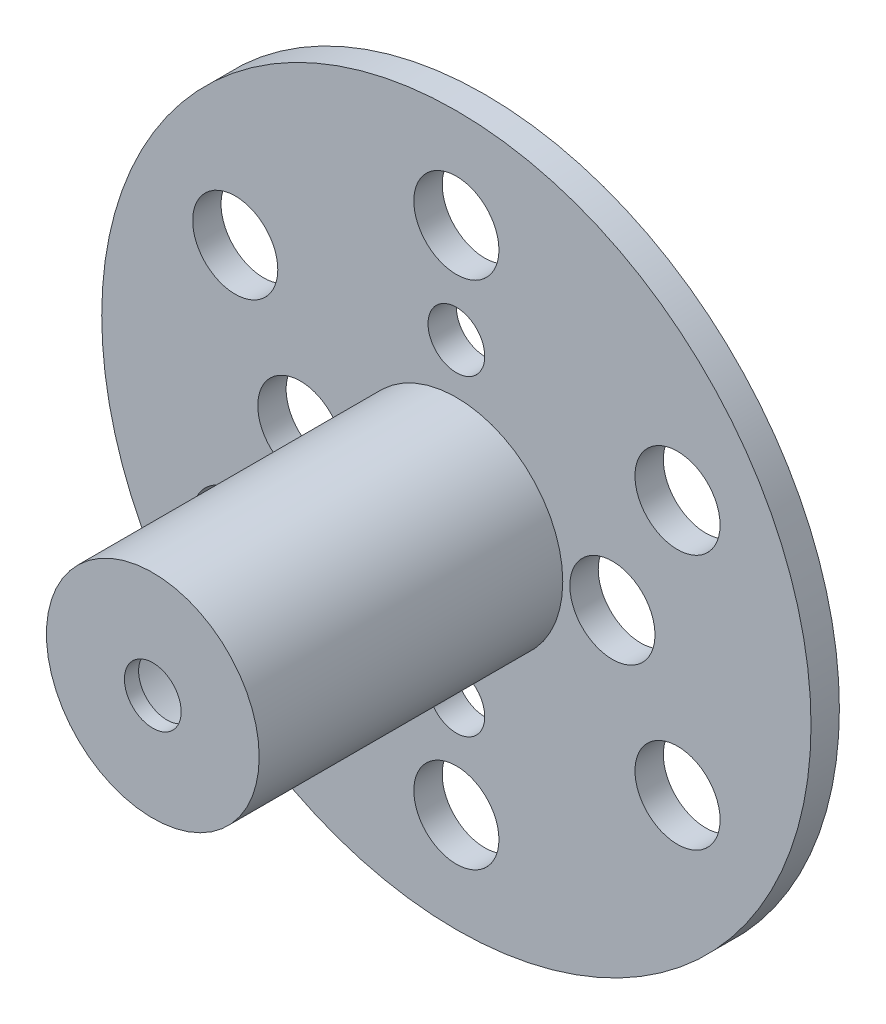
SolidWorks part; units mm, degrees
material "ABS"
ref_plane "Спереди" through (0, 0, 0) normal (0, 0, 1) x (1, 0, 0)
ref_plane "Сверху" through (0, 0, 0) normal (0, 1, 0) x (1, 0, 0)
ref_plane "Справа" through (0, 0, 0) normal (1, 0, 0) x (0, 0, -1)
sketch "Эскиз1" plane through (0, 0, 0) normal (0, 0, 1) x (1, 0, 0)
  line L0 (0, 0) -> (0, 9) construction
  line L1 (0, 0) -> (-50000, 0) construction
  circle A0 centre (0, 0) radius 2.75
  circle A1 centre (0, 0) radius 12.5
  circle A2 centre (0, 9) radius 1.5
  circle A3 centre (7.7942, 4.5) radius 1.5
  circle A4 centre (7.7942, -4.5) radius 1.5
  circle A5 centre (0, -9) radius 1.5
  circle A6 centre (-7.7942, -4.5) radius 1.5
  circle A7 centre (-7.7942, 4.5) radius 1.5
  circle A8 centre (-5.5, 0) radius 1.5
  circle A9 centre (5.5, 0) radius 1.5
  circle A10 centre (0, 0) radius 7 construction
  circle A11 centre (0, 5.5) radius 1
  circle A12 centre (0, -5.5) radius 1
  dimension "D1" = 5.5
  dimension "D2" = 25
  dimension "D4" = 3
  dimension "D7" = 3
  dimension "D9" = 2
  dimension "D3" = 9
  dimension "D6" = 9
  dimension "D8" = 5.5
  dimension "D10" = 5.5
  dimension "D5" = 6
extrude "Бобышка-Вытянуть1" add sketch "Эскиз1" along normal blind 1
sketch "Эскиз2" plane through (0, 0, 1) normal (0, 0, 1) x (1, 0, 0)
  circle A0 centre (0, 0) radius 2.75
  circle A1 centre (0, 0) radius 3.75
  dimension "D1" = 1
extrude "Бобышка-Вытянуть2" add sketch "Эскиз2" along normal blind 10.2
sketch "Эскиз3" plane through (0, 0, 11.2) normal (0, 0, 1) x (1, 0, 0)
  circle A0 centre (0, 0) radius 3.75
  circle A1 centre (0, 0) radius 1
  dimension "D1" = 7.5
  dimension "D2" = 2
extrude "Бобышка-Вытянуть3" add sketch "Эскиз3" along normal blind 0.5
